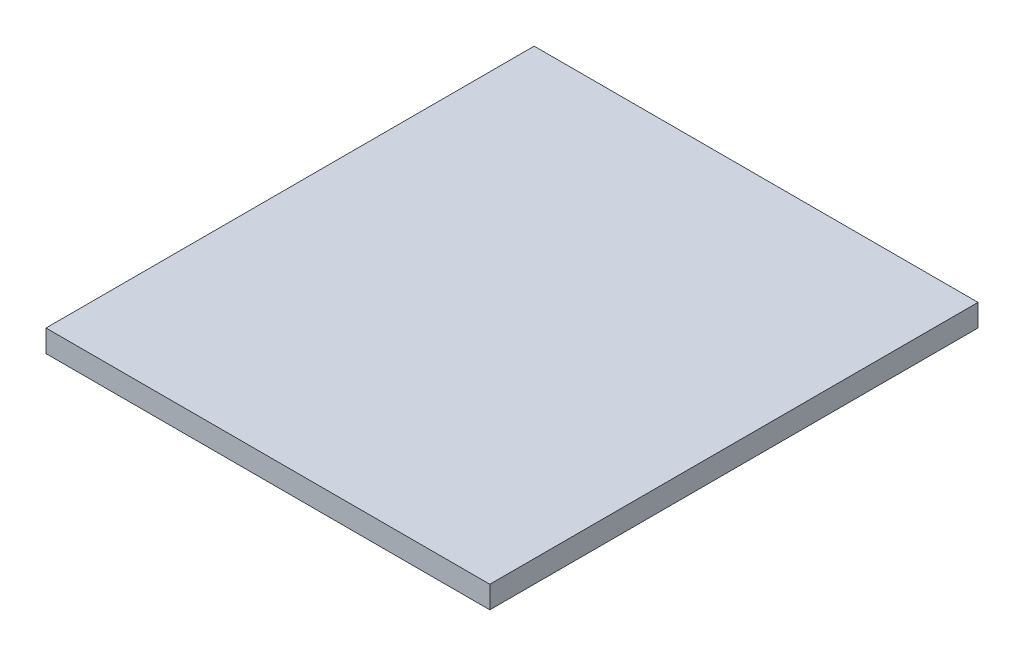
SolidWorks part; units mm, degrees
ref_plane "Alzado" through (0, 0, 0) normal (0, 0, 1) x (1, 0, 0)
ref_plane "Planta" through (0, 0, 0) normal (0, 1, 0) x (1, 0, 0)
ref_plane "Vista lateral" through (0, 0, 0) normal (1, 0, 0) x (0, 0, -1)
ref_plane "Plano1"
sketch "Croquis1" plane through (0, 0, 0) normal (0, 1, 0) x (-1, 0, 0)
  line L0 (-1, 1.1) -> (-1, -1.1)
  line L1 (-1, -1.1) -> (1, -1.1)
  line L2 (1, -1.1) -> (1, 1.1)
  line L3 (1, 1.1) -> (-1, 1.1)
  dimension "D1" = 2
  dimension "D2" = 2.2
extrude "Extrusión1" add sketch "Croquis1" along normal blind 0.1
